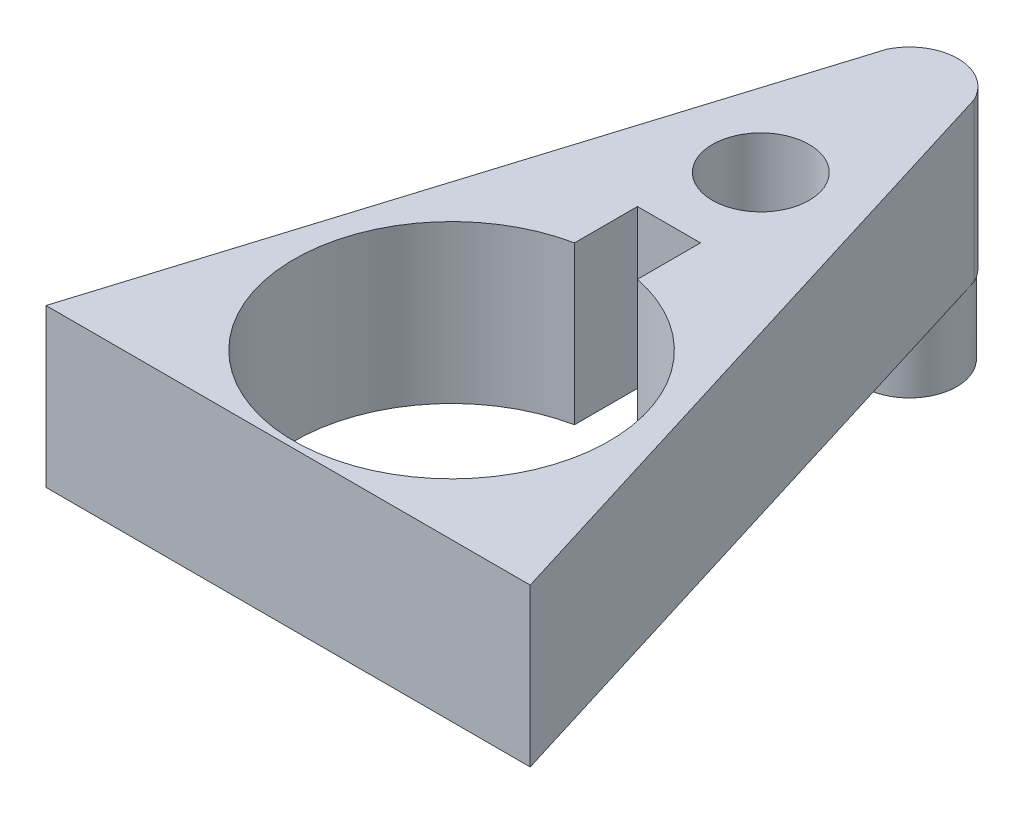
SolidWorks part; units mm, degrees
ref_plane "前视基准面" through (0, 0, 0) normal (0, 0, 1) x (1, 0, 0)
ref_plane "上视基准面" through (0, 0, 0) normal (0, 1, 0) x (1, 0, 0)
ref_plane "右视基准面" through (0, 0, 0) normal (1, 0, 0) x (0, 0, -1)
sketch "草图1" plane through (0, 0, 0) normal (0, 1, 0) x (1, 0, 0)
  line L0 (0, 0) -> (30.7332, 0)
  line L1 (30.7332, 0) -> (18.1417, 40.7606)
  line L2 (0, 0) -> (12.5915, 40.7606)
  arc A0 (18.1417, 40.7606) -> (12.5915, 40.7606) centre (15.3666, 39.44) ccw
  circle A1 centre (15.3666, 30) radius 3.0733
  dimension "D1" = 30
extrude "凸台-拉伸1" add sketch "草图1" along normal blind 10
sketch "草图2" plane through (0, 0, 0) normal (0, -1, 0) x (1, 0, 0)
  circle A0 centre (15.3666, -39.44) radius 3
extrude "凸台-拉伸2" add sketch "草图2" along normal blind 5
sketch "草图3" plane through (0, 10, 0) normal (0, 1, 0) x (1, 0, 0)
  line L0 (15.3271, 10.4141) -> (15.3271, 24.0333) construction
  line L2 (13.3271, 20.212) -> (13.3271, 24.212)
  line L3 (13.3271, 24.212) -> (17.3271, 24.212)
  line L4 (17.3271, 20.212) -> (17.3271, 24.212)
  arc A0 (13.3271, 20.212) -> (17.3271, 20.212) centre (15.3271, 10.4141) ccw
  point P9 (15.3271, 24.212)
  dimension "D1" = 10
  dimension "D2" = 4
  dimension "D3" = 4
extrude "切除-拉伸1" cut sketch "草图3" against normal blind 10
